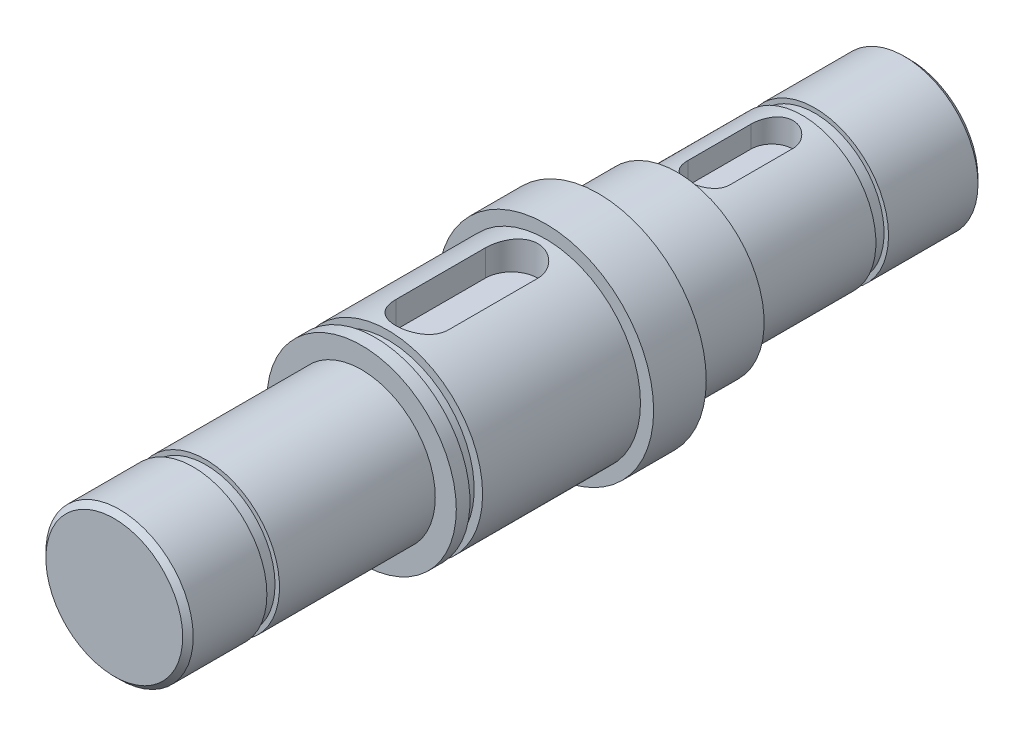
SolidWorks part; units mm, degrees
ref_plane "Ön Düzlem" through (0, 0, 0) normal (0, 0, 1) x (1, 0, 0)
ref_plane "Üst Düzlem" through (0, 0, 0) normal (0, 1, 0) x (1, 0, 0)
ref_plane "Sağ Düzlem" through (0, 0, 0) normal (1, 0, 0) x (0, 0, -1)
sketch "Sketch1" plane through (0, 0, 0) normal (0, 0, 1) x (1, 0, 0)
  circle A0 centre (0, 0) radius 18
  dimension "D1" = 36
extrude "Boss-Extrude1" add sketch "Sketch1" against normal blind 40 and the other way blind 5
sketch "Sketch2" plane through (0, 0, -40) normal (0, 0, -1) x (-1, 0, 0)
  circle A1 centre (0, 0) radius 14
  arc A2 (-4, 13.4164) -> (4, 13.4164) centre (0, 0) ccw construction
extrude "Boss-Extrude2" add sketch "Sketch2" along normal blind 45
sketch "Sketch3" plane through (0, 0, -85) normal (0, 0, -1) x (-1, 0, 0)
  circle A0 centre (0, 0) radius 14
  dimension "D1" = 28
extrude "Boss-Extrude3" add sketch "Sketch3" along normal blind 15
sketch "Sketch4" plane through (0, 0, 5) normal (0, 0, 1) x (1, 0, 0)
  circle A1 centre (0, 0) radius 14 construction
  circle A2 centre (0, 0) radius 14
extrude "Boss-Extrude4" add sketch "Sketch4" along normal blind 47
sketch "Sketch5" plane through (0, 21.3, 0) normal (0, -1, 0) x (1, 0, 0)
  line L2 (18, 5) -> (-18, 5) construction
  line L4 (5, 0) -> (-5, 0)
  line L5 (-5, 0) -> (-5, -30)
  line L6 (-5, -30) -> (5, -30)
  line L7 (5, -30) -> (5, 0)
  line L9 (-5, -6.5) -> (-5, -23.5)
  line L11 (5, -23.5) -> (5, -6.5)
  arc A0 (5, -6.5) -> (-5, -6.5) centre (0, -6.5) ccw
  arc A1 (-5, -23.5) -> (5, -23.5) centre (0, -23.5) ccw
  dimension "D3" = 11.5
  dimension "D2" = 17
  dimension "D1" = 0
extrude "Cut-Extrude1" cut sketch "Sketch5" along normal blind 8 from offset 1
sketch "Sketch6" plane through (0, 17.3, 0) normal (0, -1, 0) x (1, 0, 0)
  line L0 (-14, -100) -> (14, -100) construction
  line L1 (0, -100) -> (0, -73) construction
  line L9 (-4, -61) -> (-4, -73)
  line L11 (4, -73) -> (4, -61)
  arc A0 (4, -61) -> (-4, -61) centre (0, -61) ccw
  arc A1 (-4, -73) -> (4, -73) centre (0, -73) ccw
  dimension "D1" = 27
  dimension "D2" = 8
  dimension "D3" = 12
extrude "Cut-Extrude2" cut sketch "Sketch6" along normal blind 8
sketch "Sketch7" plane through (0, 0, 0) normal (0, 1, 0) x (1, 0, 0)
  line L0 (20.5, 40) -> (20.5, 30)
  line L1 (20.5, 40) -> (14.7214, 40)
  line L2 (14.7214, 40) -> (14.7214, 30)
  line L3 (14.7214, 30) -> (20.5, 30)
  line L6 (18, 40) -> (-18, 40) construction
  line L7 (0, 30.1145) -> (0, 37.9425) construction
  dimension "D1" = 10
  dimension "D2" = 20.5
revolve "Revolve1" add sketch "Sketch7" angle 360 about L7
sketch "Sketch8" plane through (0, 0, 0) normal (0, 1, 0) x (1, 0, 0)
  line L0 (25.1914, 0) -> (25.1914, -2.4)
  line L1 (25.1914, -2.4) -> (16.4, -2.4)
  line L2 (25.1914, 0) -> (16.4, 0)
  line L3 (16.4, 0) -> (16.4, -2.4)
  line L4 (0, 0) -> (0, -7.2291) construction
  line L5 (10.3018, 0) -> (14.6217, 0) construction
  dimension "D1" = 2.4
  dimension "D2" = 16.4
revolve "Cut-Revolve1" cut sketch "Sketch8" angle 360 about L4
sketch "Sketch11" plane through (0, 0, -60) normal (0, 0, 1) x (1, 0, 0)
  circle A0 centre (0, 0) radius 14
  circle A1 centre (0, 0) radius 16.5
  dimension "D1" = 33
  dimension "D2" = 28
sketch "Sketch12" plane through (0, 0, -83.7417) normal (0, 0, -1) x (-1, 0, 0)
  circle A0 centre (0, 0) radius 15.7568
  circle A1 centre (0, 0) radius 13.15
  dimension "D1" = 26.3
extrude "Cut-Extrude3" cut sketch "Sketch12" along normal blind 2.4 from offset 5 offset against normal yes
extrude "Boss-Extrude5" add sketch "Sketch11" along normal blind 10 from offset 15
sketch "Sketch15" plane through (0, 0, 0) normal (0, 1, 0) x (1, 0, 0)
  line L0 (-18, -5) -> (18, -5) construction
  line L1 (13.15, -37) -> (19.3839, -37)
  line L2 (13.15, -37) -> (13.15, -34.6)
  line L3 (13.15, -34.6) -> (19.3839, -34.6)
  line L4 (19.3839, -37) -> (19.3839, -34.6)
  line L5 (0, -52) -> (0, 0) construction
  line L6 (-14, -52) -> (14, -52) construction
  dimension "D1" = 32
  dimension "D2" = 2.4
  dimension "D3" = 13.15
revolve "Cut-Revolve2" cut sketch "Sketch15" angle 360 about L5
ref_plane "Plane1" through (0, 0, -99.1417) normal (0, 0, 1) x (1, 0, 0)
other "SurfaceCut1"
chamfer "Chamfer1" distance 1 angle 45 2 edges at (14, 0, -99.1417) (14, 0, 52)
sketch "Sketch16" plane through (0, 0, -45) normal (0, 0, -1) x (-1, 0, 0)
  circle A1 centre (0, 0) radius 16.5
  circle A2 centre (0, 0) radius 16.5
  dimension "D1" = 0
extrude "Boss-Extrude6" add sketch "Sketch16" along normal blind 10
